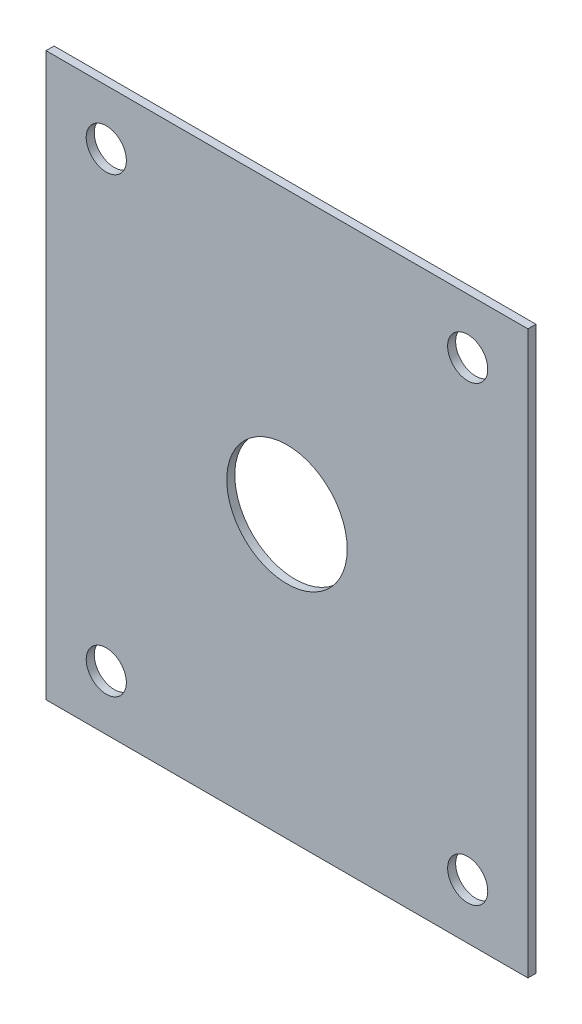
SolidWorks part; units mm, degrees
ref_plane "Front Plane" through (0, 0, 0) normal (0, 0, 1) x (1, 0, 0)
ref_plane "Top Plane" through (0, 0, 0) normal (0, 1, 0) x (1, 0, 0)
ref_plane "Right Plane" through (0, 0, 0) normal (1, 0, 0) x (0, 0, -1)
sketch "Sketch1" plane through (0, 0, 0) normal (0, 0, 1) x (1, 0, 0)
  line L1 (0, 0) -> (152.4, 0)
  line L2 (0, 0) -> (0, 177.8)
  line L3 (0, 177.8) -> (152.4, 177.8)
  line L4 (152.4, 0) -> (152.4, 177.8)
extrude "Boss-Extrude1" add sketch "Sketch1" along normal blind 2.54
sketch "Sketch2" plane through (0, 0, 0) normal (0, 0, 1) x (1, 0, 0)
  line L0 (76.2, 177.8) -> (76.2, 0) construction
  line L1 (152.4, 177.8) -> (0, 177.8) construction
  line L2 (0, 0) -> (152.4, 0) construction
  line L3 (0, 88.9) -> (152.4, 88.9) construction
  line L4 (0, 177.8) -> (0, 0) construction
  line L5 (152.4, 0) -> (152.4, 177.8) construction
  circle A0 centre (76.2, 88.9) radius 19.05
extrude "Cut-Extrude1" cut sketch "Sketch2" along normal through all
sketch "Sketch3" plane through (0, 0, 0) normal (0, 0, 1) x (1, 0, 0)
  line L0 (76.2, 177.8) -> (76.2, 0) construction
  line L1 (152.4, 177.8) -> (0, 177.8) construction
  line L2 (0, 0) -> (152.4, 0) construction
  line L3 (76.2, 88.9) -> (0, 88.9) construction
  line L4 (0, 177.8) -> (0, 0) construction
  line L5 (76.2, 88.9) -> (152.4, 88.9) construction
  line L6 (152.4, 0) -> (152.4, 177.8) construction
  line L7 (76.2, 88.9) -> (76.2, 160.401) construction
  line L8 (76.2, 160.401) -> (19.05, 160.401) construction
  circle A0 centre (19.05, 160.401) radius 6.35
  circle A1 centre (133.35, 160.401) radius 6.35
  circle A2 centre (133.35, 17.399) radius 6.35
  circle A3 centre (19.05, 17.399) radius 6.35
extrude "Cut-Extrude3" cut sketch "Sketch3" along normal through all
